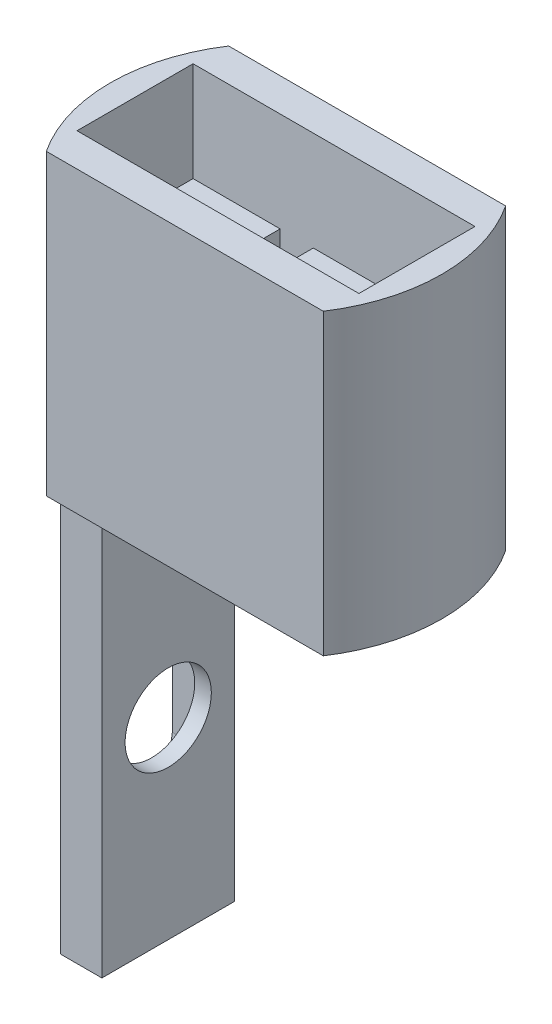
SolidWorks part; units mm, degrees
ref_plane "Front Plane" through (0, 0, 0) normal (0, 0, 1) x (1, 0, 0)
ref_plane "Top Plane" through (0, 0, 0) normal (0, 1, 0) x (1, 0, 0)
ref_plane "Right Plane" through (0, 0, 0) normal (1, 0, 0) x (0, 0, -1)
sketch "Sketch3" plane through (0, 0, 0) normal (0, 1, 0) x (1, 0, 0)
  circle A0 centre (0, 0) radius 10
  dimension "D1" = 20
extrude "Boss-Extrude1" add sketch "Sketch3" along normal blind 18
sketch "Sketch4" plane through (0, 0, 0) normal (0, -1, 0) x (-1, 0, 0)
  line L1 (9, 4) -> (6.5, 4)
  line L2 (9, 4) -> (9, -4)
  line L3 (9, -4) -> (6.5, -4)
  line L4 (6.5, 4) -> (6.5, -4)
  line L5 (9, 4) -> (6.5, -4) construction
  line L6 (9, -4) -> (6.5, 4) construction
  point P0 (7.75, 0)
  dimension "D1" = 2.5
  dimension "D2" = 8
  dimension "D3" = 7.75
extrude "Boss-Extrude2" add sketch "Sketch4" along normal blind 25
sketch "Sketch5" plane through (-6.5, 0, 0) normal (1, 0, 0) x (0, 0, -1)
  line L0 (-4, -25) -> (4, -25) construction
  circle A0 centre (0, -13.4) radius 2.6
  dimension "D1" = 5.2
  dimension "D2" = 11.6
extrude "Cut-Extrude1" cut sketch "Sketch5" against normal up to next
sketch "Sketch7" plane through (0, 18, 0) normal (0, 1, 0) x (1, 0, 0)
  line L0 (-10, 0) -> (10, 0) construction
  line L1 (-8.5, -3.5) -> (8.5, -3.5)
  line L2 (-8.5, -3.5) -> (-8.5, 3.5)
  line L3 (-8.5, 3.5) -> (8.5, 3.5)
  line L4 (8.5, -3.5) -> (8.5, 3.5)
  circle A0 centre (0, 0) radius 10 construction
  point P4 (-8.5, 0)
  dimension "D1" = 7
  dimension "D2" = 17
  dimension "D3" = 1.5
extrude "Cut-Extrude3" cut sketch "Sketch7" against normal blind 6
sketch "Sketch8" plane through (0, 12, 0) normal (0, 1, 0) x (1, 0, 0)
  line L0 (8.5, 0) -> (-1.25, 0) construction
  line L1 (8.5, -3.5) -> (8.5, 3.5) construction
  line L2 (8.5, 3.5) -> (-8.5, 3.5) construction
  line L3 (-1.25, 3.5) -> (-3.25, 3.5)
  line L4 (-1.25, 3.5) -> (-1.25, -3.5)
  line L5 (-1.25, -3.5) -> (-3.25, -3.5)
  line L6 (-3.25, 3.5) -> (-3.25, -3.5)
  line L7 (-8.5, 3.5) -> (-8.5, -3.5) construction
  dimension "D1" = 9.75
  dimension "D2" = 2
extrude "Cut-Extrude4" cut sketch "Sketch8" against normal blind 4
sketch "Sketch11" plane through (-9, 0, 0) normal (-1, 0, 0) x (0, 0, 1)
  line L0 (-2.75, -2.9) -> (2.75, -23.9) construction
  line L1 (2.75, -23.9) -> (-2.75, -23.9)
  line L2 (2.75, -23.9) -> (2.75, -2.9)
  line L3 (2.75, -2.9) -> (-2.75, -2.9)
  line L4 (-2.75, -23.9) -> (-2.75, -2.9)
  line L5 (-2.75, -23.9) -> (2.75, -2.9) construction
  line L6 (-2.6, -13.4) -> (2.6, -13.4) construction
  line L7 (0, -10.8) -> (0, -16) construction
  circle A0 centre (0, -13.4) radius 2.6 construction
  point P11 (0, -13.4)
  point P12 (0, -13.4)
  dimension "D1" = 5.5
  dimension "D2" = 21
extrude "Cut-Extrude7" cut sketch "Sketch11" against normal blind 1.5
sketch "Sketch9" plane through (0, 0, 0) normal (0, -1, 0) x (1, 0, 0)
  line L0 (8.3516, -5.5) -> (-8.3516, -5.5)
  line L1 (-9, -4) -> (-6.5, -4) construction
  line L2 (0, -5.5) -> (0, -4) construction
  line L3 (8.3516, 5.5) -> (-8.3516, 5.5)
  line L4 (0, 4) -> (0, 5.5) construction
  circle A0 centre (0, 0) radius 10 construction
  arc A1 (8.3516, -5.5) -> (-8.3516, -5.5) centre (0, 0) cw
  arc A2 (-8.3516, 5.5) -> (8.3516, 5.5) centre (0, 0) cw
  dimension "D1" = 1.5
extrude "Cut-Extrude5" cut sketch "Sketch9" against normal blind 43
sketch "Sketch10" plane through (-9, 0, 0) normal (-1, 0, 0) x (0, 0, 1)
  line L0 (-2.75, -23.9) -> (-2.75, -16.8)
  line L1 (-2.75, -16.8) -> (-1.5, -23.9)
  line L2 (-1.5, -23.9) -> (-2.75, -23.9)
  line L3 (-2.75, -13.4) -> (2.75, -13.4) construction
  line L4 (0, -23.9) -> (0, -2.9) construction
  line L5 (1.5, -23.9) -> (2.75, -23.9)
  line L6 (2.75, -16.8) -> (1.5, -23.9)
  line L7 (2.75, -23.9) -> (2.75, -16.8)
  line L8 (2.75, -2.9) -> (2.75, -10)
  line L9 (2.75, -10) -> (1.5, -2.9)
  line L10 (1.5, -2.9) -> (2.75, -2.9)
  line L11 (-1.5, -2.9) -> (-2.75, -2.9)
  line L12 (-2.75, -10) -> (-1.5, -2.9)
  line L13 (-2.75, -2.9) -> (-2.75, -10)
  line L14 (0, -10.8) -> (0, -16) construction
  line L15 (2.6, -13.4) -> (-2.6, -13.4) construction
  line L16 (4, 0) -> (-4, 0) construction
  line L17 (-4, -25) -> (-4, 0) construction
  circle A0 centre (0, -13.4) radius 2.6 construction
  dimension "D1" = 1.25
  dimension "D2" = 2.5
  dimension "D3" = 2.9
  dimension "D4" = 10
extrude "Boss-Extrude3" add sketch "Sketch10" against normal blind 1.5
